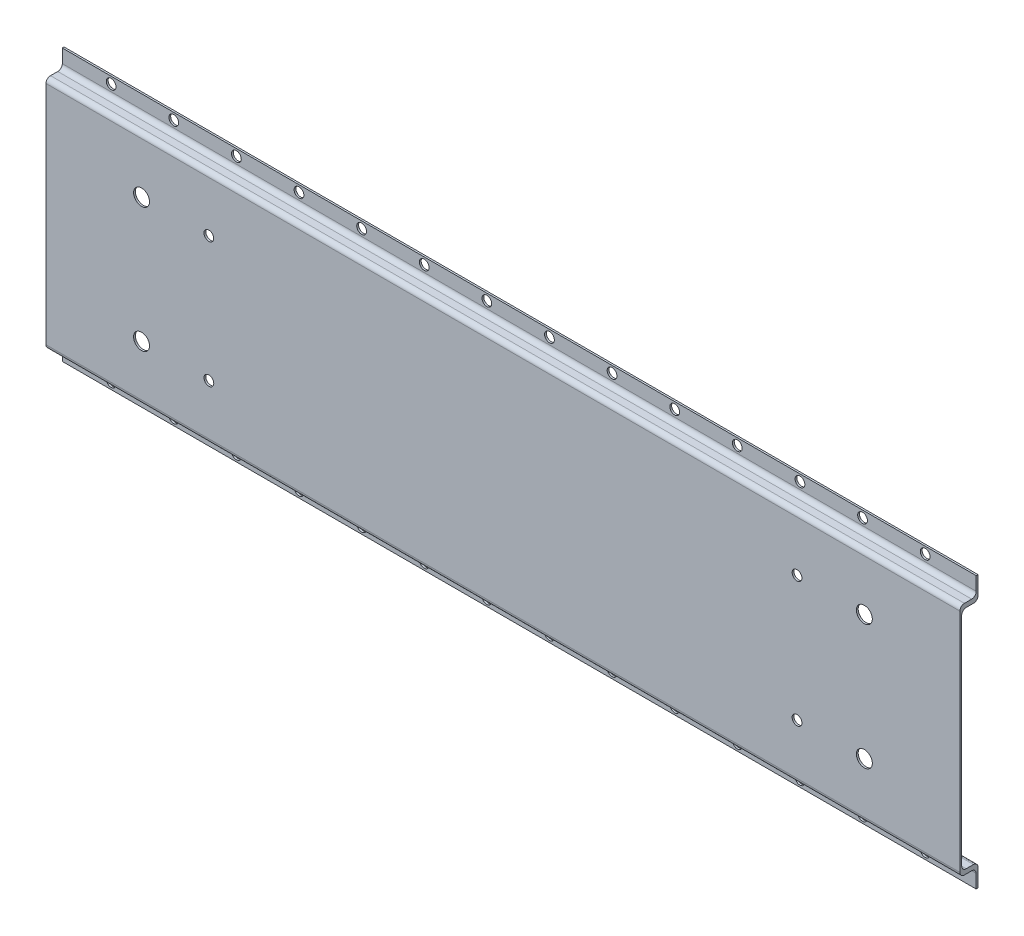
SolidWorks part; units mm, degrees
material "AISI 316 Stainless Steel Sheet (SS)"
ref_plane "Front Plane" through (0, 0, 0) normal (0, 0, 1) x (1, 0, 0)
ref_plane "Top Plane" through (0, 0, 0) normal (0, 1, 0) x (1, 0, 0)
ref_plane "Right Plane" through (0, 0, 0) normal (1, 0, 0) x (0, 0, -1)
sketch "Sketch1" plane through (0, 0, 0) normal (0, 0, 1) x (1, 0, 0)
  line L1 (-320.675, -95.25) -> (320.675, -95.25)
  line L2 (-320.675, -95.25) -> (-320.675, 95.25)
  line L3 (-320.675, 95.25) -> (320.675, 95.25)
  line L4 (320.675, -95.25) -> (320.675, 95.25)
  line L5 (-320.675, -95.25) -> (320.675, 95.25) construction
  line L6 (-320.675, 95.25) -> (320.675, -95.25) construction
  point P0 (0, 0)
  dimension "D1" = 641.35
  dimension "D2" = 190.5
extrude "Boss-Extrude1" add sketch "Sketch1" along normal blind 12.7
sketch "Sketch2" plane through (0, 0, 12.7) normal (0, 0, 1) x (1, 0, 0)
  line L0 (320.675, -95.25) -> (320.675, 95.25) construction
  line L1 (-320.675, 95.25) -> (320.675, 95.25)
  line L2 (-320.675, 95.25) -> (-320.675, 82.55)
  line L3 (-320.675, 82.55) -> (320.675, 82.55)
  line L4 (320.675, 95.25) -> (320.675, 82.55)
  line L6 (-320.675, -95.25) -> (320.675, -95.25)
  line L7 (-320.675, -95.25) -> (-320.675, -82.55)
  line L8 (-320.675, -82.55) -> (320.675, -82.55)
  line L9 (320.675, -95.25) -> (320.675, -82.55)
  dimension "D1" = 12.7
  dimension "D2" = 12.7
extrude "Cut-Extrude1" cut sketch "Sketch2" against normal blind 11.43 contours L2 L1 L4 L3 | L7 L6 L9 L8
sketch "Sketch4" plane through (0, 0, 0) normal (0, 0, -1) x (-1, 0, 0)
  line L0 (320.675, 95.25) -> (320.675, -95.25) construction
  line L1 (-320.675, -79.375) -> (320.675, -79.375)
  line L2 (-320.675, -79.375) -> (-320.675, 79.375)
  line L3 (-320.675, 79.375) -> (320.675, 79.375)
  line L4 (320.675, -79.375) -> (320.675, 79.375)
  line L5 (-320.675, -79.375) -> (320.675, 79.375) construction
  line L6 (-320.675, 79.375) -> (320.675, -79.375) construction
  point P0 (0, 0)
  dimension "D1" = 158.75
extrude "Cut-Extrude2" cut sketch "Sketch4" against normal blind 11.43 contours L2 L1 L4 L3
fillet "Fillet2" radius 3.175 8 edges at (0, -79.375, 11.43) (0, -82.55, 1.27) (0, -82.55, 12.7) (0, -79.375, 0) (0, 82.55, 1.27) (0, 82.55, 12.7) (0, 79.375, 11.43) (0, 79.375, 0)
sketch "Sketch6" plane through (0, 0, 1.27) normal (0, 0, 1) x (1, 0, 0)
  line L3 (-320.675, 0) -> (-242.443, 0)
  line L5 (-320.675, 79.375) -> (-320.675, -79.375) construction
  circle A0 centre (-286.385, 90.4875) radius 3.429
  circle A1 centre (-242.443, 90.4875) radius 3.429
  circle A2 centre (-198.501, 90.4875) radius 3.429
  circle A3 centre (-154.559, 90.4875) radius 3.429
  circle A4 centre (-110.617, 90.4875) radius 3.429
  circle A5 centre (-66.675, 90.4875) radius 3.429
  circle A6 centre (-22.733, 90.4875) radius 3.429
  circle A7 centre (21.209, 90.4875) radius 3.429
  circle A8 centre (65.151, 90.4875) radius 3.429
  circle A9 centre (109.093, 90.4875) radius 3.429
  circle A10 centre (153.035, 90.4875) radius 3.429
  circle A11 centre (196.977, 90.4875) radius 3.429
  circle A12 centre (240.919, 90.4875) radius 3.429
  circle A13 centre (284.861, 90.4875) radius 3.429
  circle A14 centre (284.861, -90.4875) radius 3.429
  circle A15 centre (240.919, -90.4875) radius 3.429
  circle A16 centre (196.977, -90.4875) radius 3.429
  circle A17 centre (153.035, -90.4875) radius 3.429
  circle A18 centre (109.093, -90.4875) radius 3.429
  circle A19 centre (65.151, -90.4875) radius 3.429
  circle A20 centre (21.209, -90.4875) radius 3.429
  circle A21 centre (-22.733, -90.4875) radius 3.429
  circle A22 centre (-66.675, -90.4875) radius 3.429
  circle A23 centre (-110.617, -90.4875) radius 3.429
  circle A24 centre (-154.559, -90.4875) radius 3.429
  circle A25 centre (-198.501, -90.4875) radius 3.429
  circle A26 centre (-242.443, -90.4875) radius 3.429
  circle A27 centre (-286.385, -90.4875) radius 3.429
  point P61 (0, 0)
  point P62 (0, 0)
  dimension "D2" = 6.858
  dimension "D1" = 14
extrude "Cut-Extrude3" cut sketch "Sketch6" against normal blind 11.43 contours A0 | A1 | A2 | A3 | A4 | A5 | A13 | A12 | A11 | A10 | A9 | A8 | A7 | A27 | A26 | A25 | A24 | A23 | A22 | A21 | A20 | A19 | A18 | A17 | A16 | A15 | A14 | A6
sketch "Sketch8" plane through (0, 0, 12.7) normal (0, 0, 1) x (1, 0, 0)
  line L0 (0, 0) -> (0, 40.2964)
  line L2 (0, 0) -> (43.1554, 0)
  circle A0 centre (-253.619, 43.815) radius 5.588
  circle A1 centre (253.619, 43.815) radius 5.588
  circle A2 centre (253.619, -43.815) radius 5.588
  circle A3 centre (-253.619, -43.815) radius 5.588
  point P12 (0, 0)
  dimension "D1" = 11.176
extrude "Cut-Extrude4" cut sketch "Sketch8" against normal blind 11.43 contours A0 | A3 | A1 | A2
sketch "Sketch9" plane through (0, 0, 12.7) normal (0, 0, 1) x (1, 0, 0)
  line L0 (0, 0) -> (32.6659, 0)
  line L2 (0, 0) -> (0, 30.4276)
  circle A0 centre (-206.375, 44.0153) radius 3.429
  circle A1 centre (206.375, 44.0153) radius 3.429
  circle A2 centre (206.375, -44.0153) radius 3.429
  circle A3 centre (-206.375, -44.0153) radius 3.429
  dimension "D2" = 6.858
extrude "Cut-Extrude5" cut sketch "Sketch9" against normal blind 11.43 contours A0 | A3 | A1 | A2
